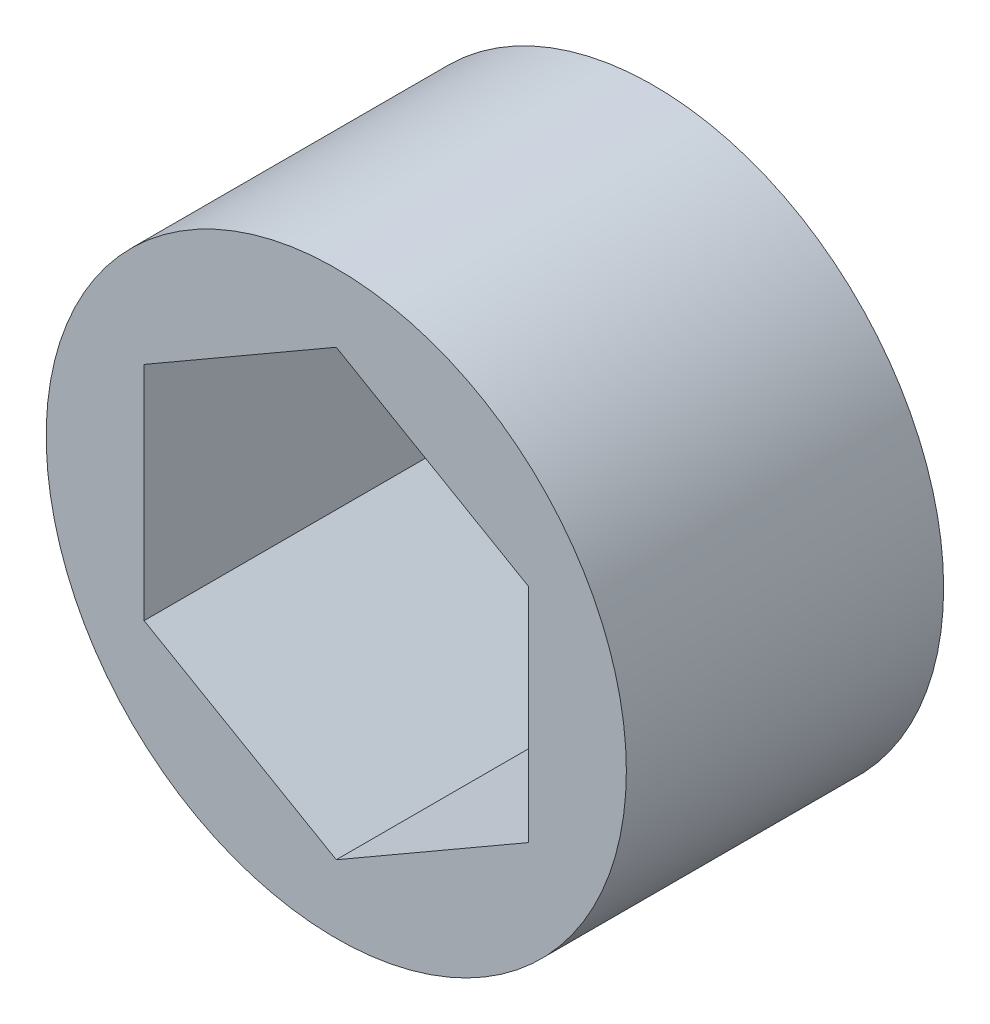
SolidWorks part; units mm, degrees
material "Nylon 101"
ref_plane "Front Plane" through (0, 0, 0) normal (0, 0, 1) x (1, 0, 0)
ref_plane "Top Plane" through (0, 0, 0) normal (0, 1, 0) x (1, 0, 0)
ref_plane "Right Plane" through (0, 0, 0) normal (1, 0, 0) x (0, 0, -1)
sketch "Sketch1" plane through (0, 0, 0) normal (0, 0, 1) x (1, 0, 0)
  line L1 (0, 7.7723) -> (-6.731, 3.8861)
  line L2 (-6.731, 3.8861) -> (-6.731, -3.8861)
  line L3 (-6.731, -3.8861) -> (0, -7.7723)
  line L4 (0, -7.7723) -> (6.731, -3.8861)
  line L5 (6.731, -3.8861) -> (6.731, 3.8861)
  line L6 (6.731, 3.8861) -> (0, 7.7723)
  circle A0 centre (0, 0) radius 10.16
  circle A1 centre (0, 0) radius 6.731 construction
  point P3 (0, 0)
  dimension "D1" = 20.32
  dimension "D2" = 13.462
extrude "Boss-Extrude1" add sketch "Sketch1" along normal mid plane 11.1125
